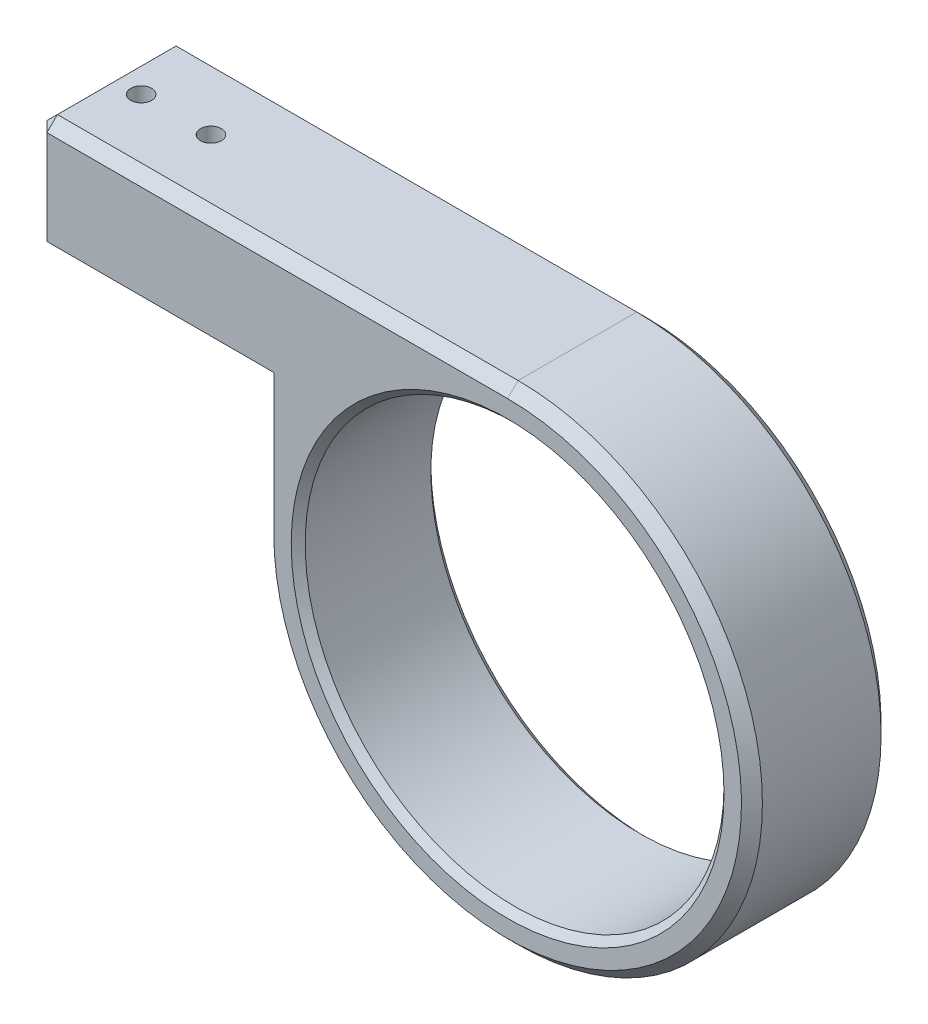
SolidWorks part; units mm, degrees
ref_plane "Front" through (0, 0, 0) normal (0, 0, 1) x (1, 0, 0)
ref_plane "Top" through (0, 0, 0) normal (0, 1, 0) x (1, 0, 0)
ref_plane "Right" through (0, 0, 0) normal (1, 0, 0) x (0, 0, -1)
sketch "草图1" plane through (0, 0, 0) normal (0, 0, 1) x (1, 0, 0)
  circle A0 centre (0, 0) radius 35
  dimension "D1" = 70
extrude "凸台-拉伸1" add sketch "草图1" along normal blind 20
sketch "草图2" plane through (0, 0, 0) normal (0, 0, -1) x (-1, 0, 0)
  circle A0 centre (0, 0) radius 30
  dimension "D1" = 60
extrude "切除-拉伸1" cut sketch "草图2" against normal through all
ref_plane "基准面1" through (-35, 0, 0) normal (-1, 0, 0) x (0, 0, 1)
sketch "草图3" plane through (-35, 0, 0) normal (-1, 0, 0) x (0, 0, 1)
  line L0 (0, 35) -> (0, -35) construction
  line L1 (20, 20) -> (0, 20)
  line L2 (20, 20) -> (20, 35)
  line L3 (20, 35) -> (0, 35)
  line L4 (0, 20) -> (0, 35)
  line L5 (20, 20) -> (0, 35) construction
  line L6 (20, 35) -> (0, 20) construction
  line L7 (20, -35) -> (20, 35) construction
  line L8 (0, 0) -> (20, 0) construction
  point P0 (10, 27.5)
  dimension "D1" = 20
  dimension "D2" = 15
extrude "凸台-拉伸2" add sketch "草图3" against normal up to surface (6.2772 mm away)
sketch "草图4" plane through (-35, 0, 0) normal (-1, 0, 0) x (0, 0, 1)
  line L0 (20, 35) -> (0, 35) construction
  line L1 (20, 20) -> (0, 20)
  line L2 (20, 20) -> (20, 35)
  line L3 (20, 35) -> (0, 35)
  line L4 (0, 20) -> (0, 35)
  line L5 (20, 20) -> (0, 35) construction
  line L6 (20, 35) -> (0, 20) construction
  line L7 (0, 35) -> (0, 20) construction
  line L8 (20, 20) -> (20, 35) construction
  line L9 (0, 20) -> (20, 20) construction
  point P0 (10, 27.5)
extrude "凸台-拉伸3" add sketch "草图4" along normal blind 32.5
sketch "草图6" plane through (-35, 0, 0) normal (-1, 0, 0) x (0, 0, 1)
  line L1 (20, 0) -> (0, 0)
  line L2 (20, 0) -> (20, 20)
  line L3 (20, 20) -> (0, 20)
  line L4 (0, 0) -> (0, 20)
  line L5 (20, 0) -> (0, 20) construction
  line L6 (20, 20) -> (0, 0) construction
  line L7 (0, 20) -> (20, 20) construction
  line L8 (0, 35) -> (0, -35) construction
  line L9 (20, -35) -> (20, 35) construction
  line L10 (0, 0) -> (20, 0) construction
  point P0 (10, 10)
extrude "凸台-拉伸4" add sketch "草图6" against normal up to surface up to face at (0.9202, -1.7621, 10)
sketch "草图7" plane through (0, 20, 0) normal (0, -1, 0) x (1, 0, 0)
  line L0 (-67.5, 10) -> (-35, 10) construction
  line L1 (-67.5, 0) -> (-67.5, 20) construction
  line L2 (-35, 20) -> (-35, 0) construction
  circle A0 centre (-62.5, 10) radius 1.5
  circle A1 centre (-52.5, 10) radius 1.5
  dimension "D1" = 3
  dimension "D2" = 3
  dimension "D3" = 5
  dimension "D4" = 10
extrude "切除-拉伸2" cut sketch "草图7" against normal through all
chamfer "倒角1" distance 1 angle 45 2 edges at (-30, 0, 20) (-30, 0, 0)
chamfer "倒角2" distance 1.5 angle 45 9 edges at (-67.5, 27.5, 20) (-67.5, 27.5, 0) (-35, 10, 0) (-33.75, 35, 0) (24.7487, -24.7487, 0) (-35, 10, 20) (-33.75, 35, 20) (24.7487, -24.7487, 20) (-67.5, 35, 10)
